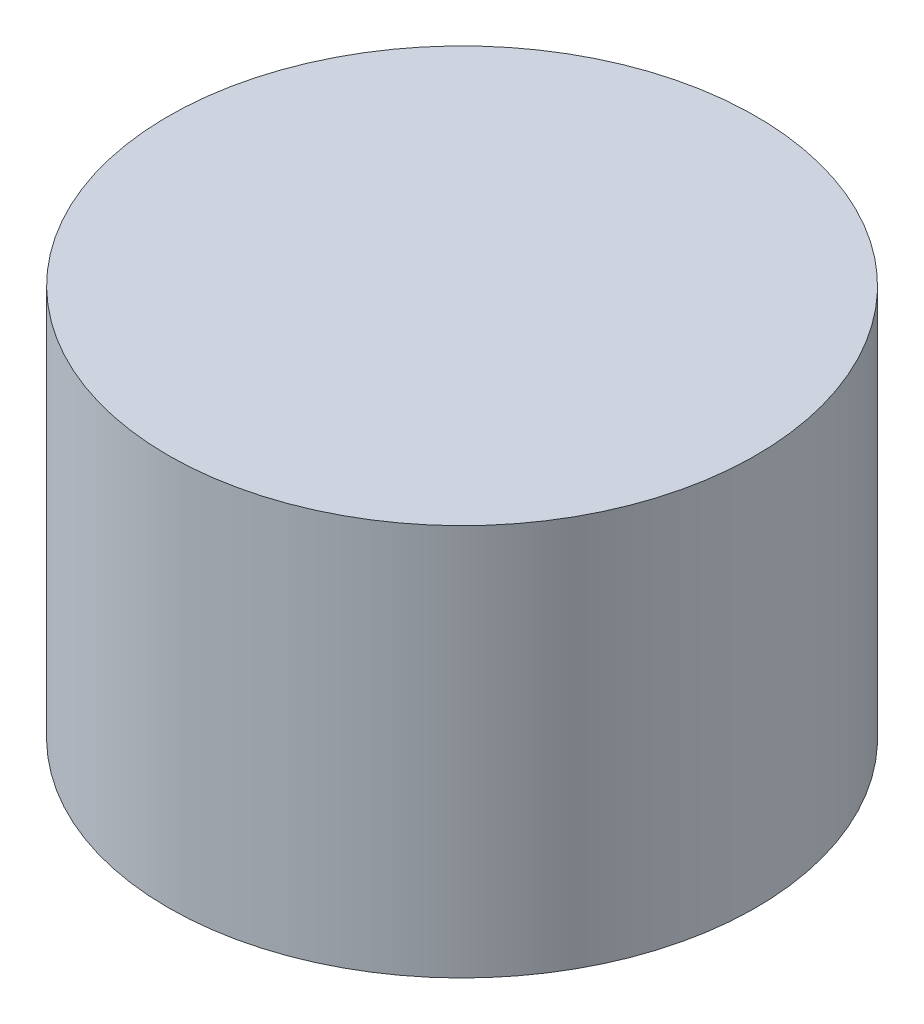
SolidWorks part; units mm, degrees
ref_plane "Front Plane" through (0, 0, 0) normal (0, 0, 1) x (1, 0, 0)
ref_plane "Top Plane" through (0, 0, 0) normal (0, 1, 0) x (1, 0, 0)
ref_plane "Right Plane" through (0, 0, 0) normal (1, 0, 0) x (0, 0, -1)
sketch "Sketch1" plane through (0, 0, 0) normal (0, 1, 0) x (1, 0, 0)
  circle A0 centre (0, 0) radius 19.05
extrude "Boss-Extrude1" add sketch "Sketch1" along normal blind 25.4 contours A0
